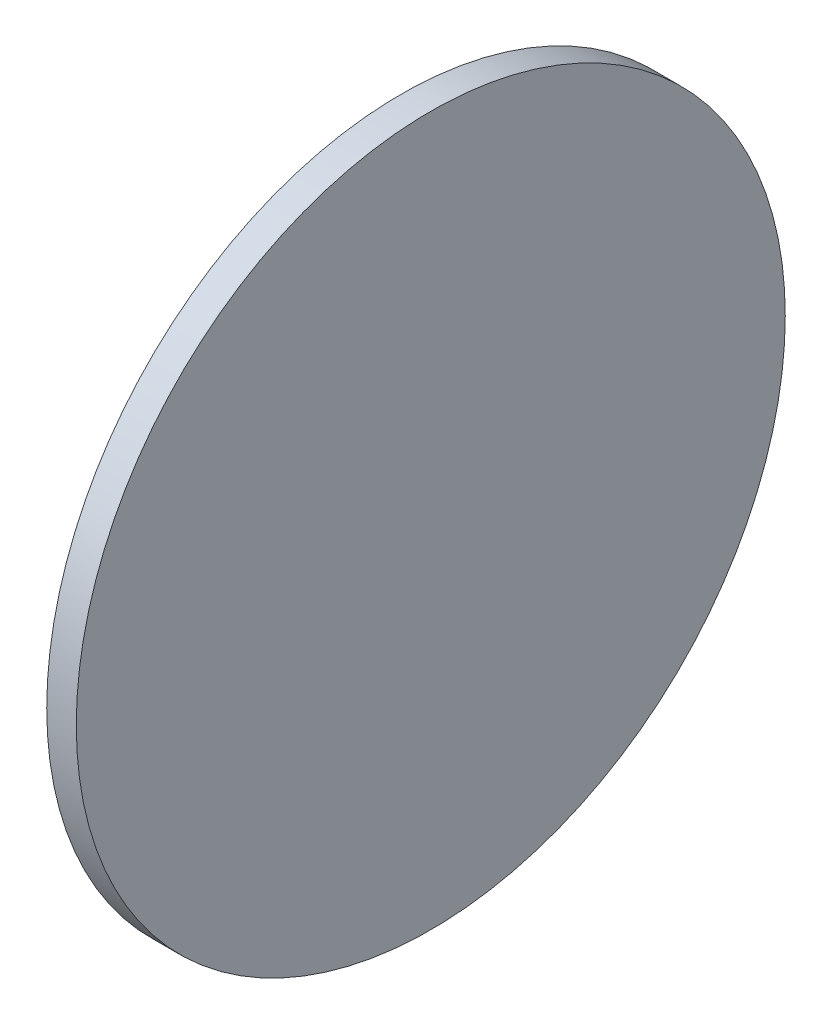
SolidWorks part; units mm, degrees
ref_plane "Front Plane" through (0, 0, 0) normal (0, 0, 1) x (1, 0, 0)
ref_plane "Top Plane" through (0, 0, 0) normal (0, 1, 0) x (1, 0, 0)
ref_plane "Right Plane" through (0, 0, 0) normal (1, 0, 0) x (0, 0, -1)
sketch "Sketch1" plane through (0, 0, 0) normal (1, 0, 0) x (0, 0, -1)
  circle A0 centre (0, 0) radius 12
  dimension "D1" = 24
extrude "Boss-Extrude1" add sketch "Sketch1" along normal blind 1
